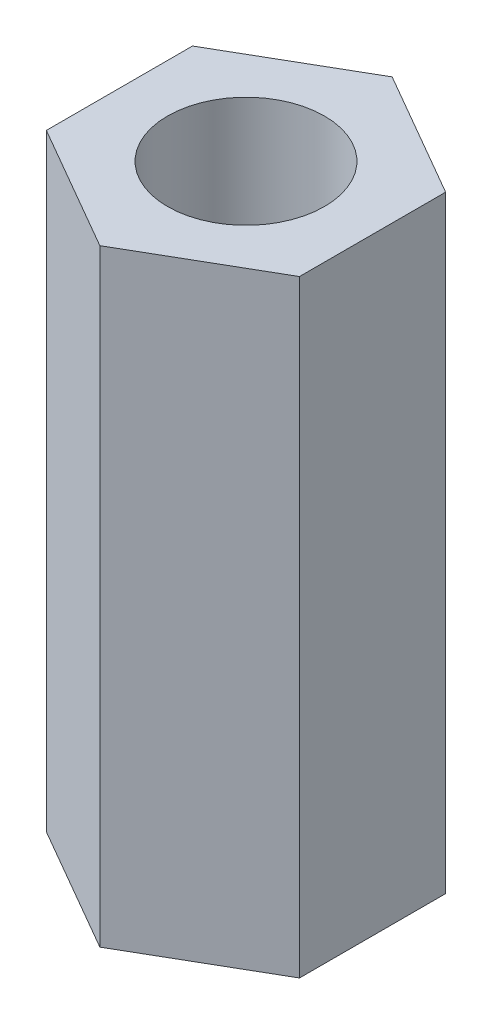
SolidWorks part; units mm, degrees
ref_plane "Front Plane" through (0, 0, 0) normal (0, 0, 1) x (1, 0, 0)
ref_plane "Top Plane" through (0, 0, 0) normal (0, 1, 0) x (1, 0, 0)
ref_plane "Right Plane" through (0, 0, 0) normal (1, 0, 0) x (0, 0, -1)
sketch "Sketch1" plane through (0, 0, 0) normal (0, 1, 0) x (1, 0, 0)
  line L0 (0, 2.887) -> (2.5002, 1.4435)
  line L1 (2.5002, 1.4435) -> (2.5002, -1.4435)
  line L2 (2.5002, -1.4435) -> (0, -2.887)
  line L3 (0, -2.887) -> (-2.5002, -1.4435)
  line L4 (-2.5002, -1.4435) -> (-2.5002, 1.4435)
  line L5 (-2.5002, 1.4435) -> (0, 2.887)
  circle A0 centre (0, 0) radius 1.55
  dimension "D2" = 3.1
  dimension "D3" = 2.887
extrude "Boss-Extrude1" add sketch "Sketch1" along normal blind 12
